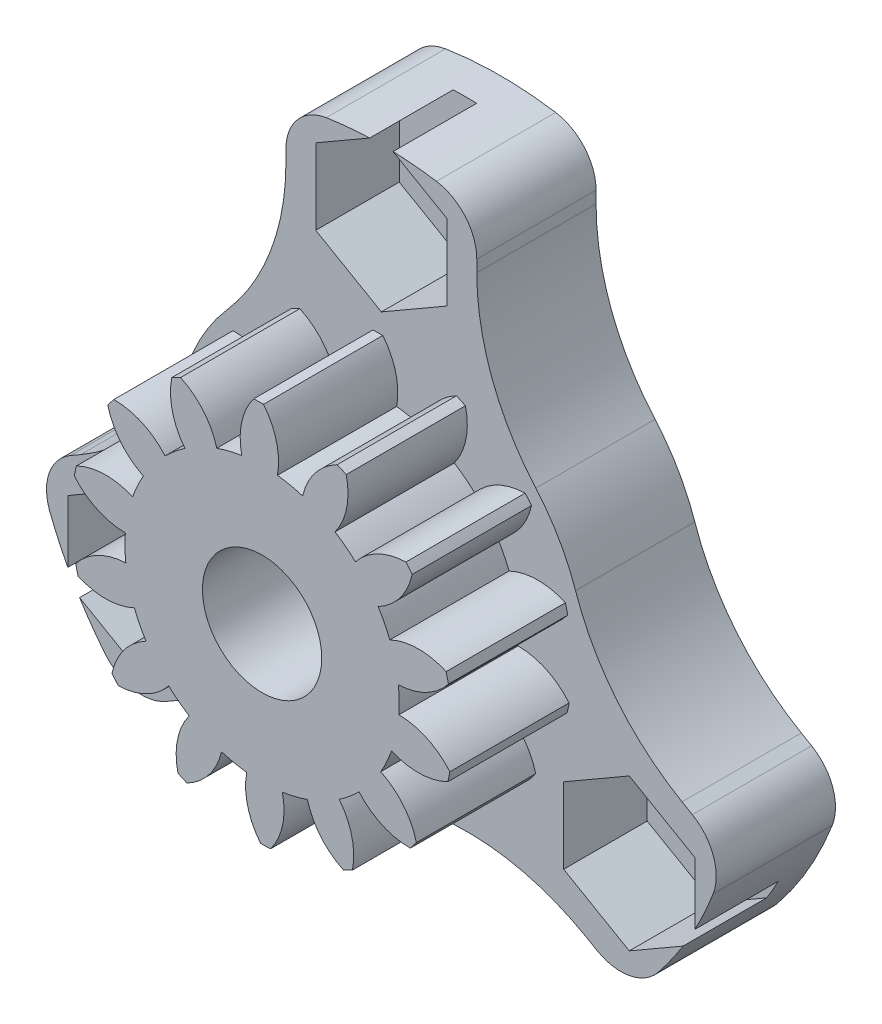
SolidWorks part; units mm, degrees
ref_plane "Front Plane" through (0, 0, 0) normal (0, 0, 1) x (1, 0, 0)
ref_plane "Top Plane" through (0, 0, 0) normal (0, 1, 0) x (1, 0, 0)
ref_plane "Right Plane" through (0, 0, 0) normal (1, 0, 0) x (0, 0, -1)
sketch "Sketch1" plane through (0, 0, 0) normal (0, 0, 1) x (1, 0, 0)
  circle A0 centre (0, 0) radius 14.9
  circle A1 centre (0, 12) radius 1.6
  circle A2 centre (10.3923, -6) radius 1.6
  circle A3 centre (-10.3923, -6) radius 1.6
  circle A4 centre (0, 0) radius 2.5
  point P11 (0, 0)
  dimension "D1" = 3
extrude "Boss-Extrude1" add sketch "Sketch1" along normal blind 5
sketch "Sketch2" plane through (0, 0, 5) normal (0, 0, 1) x (1, 0, 0)
  line L0 (13.1423, -7.5877) -> (13.1423, -4.4123)
  line L7 (0, 15.1754) -> (-2.75, 13.5877)
  line L8 (-2.75, 13.5877) -> (-2.75, 10.4123)
  line L9 (-2.75, 10.4123) -> (0, 8.8246)
  line L10 (0, 8.8246) -> (2.75, 10.4123)
  line L11 (2.75, 10.4123) -> (2.75, 13.5877)
  line L12 (2.75, 13.5877) -> (0, 15.1754)
  line L13 (13.1423, -4.4123) -> (10.3923, -2.8246)
  line L14 (10.3923, -2.8246) -> (7.6423, -4.4123)
  line L15 (7.6423, -4.4123) -> (7.6423, -7.5877)
  line L16 (7.6423, -7.5877) -> (10.3923, -9.1754)
  line L17 (10.3923, -9.1754) -> (13.1423, -7.5877)
  line L18 (-13.1423, -7.5877) -> (-10.3923, -9.1754)
  line L19 (-10.3923, -9.1754) -> (-7.6423, -7.5877)
  line L20 (-7.6423, -7.5877) -> (-7.6423, -4.4123)
  line L21 (-7.6423, -4.4123) -> (-10.3923, -2.8246)
  line L22 (-10.3923, -2.8246) -> (-13.1423, -4.4123)
  line L23 (-13.1423, -4.4123) -> (-13.1423, -7.5877)
  circle A0 centre (0, 12) radius 2.75 construction
  circle A1 centre (10.3923, -6) radius 2.75 construction
  circle A2 centre (-10.3923, -6) radius 2.75 construction
  point P27 (0, 0)
  dimension "D1" = 3
extrude "Cut-Extrude1" cut sketch "Sketch2" against normal blind 3.5
sketch "Sketch5" plane through (0, 0, 5) normal (0, 0, 1) x (1, 0, 0)
  line L7 (-8.5932, -0.3425) -> (-14.4301, -3.7124)
  line L8 (-4.5932, -7.2707) -> (-10.9038, -10.9141)
  line L9 (4.5932, -7.2707) -> (10.4301, -10.6406)
  line L10 (8.5932, -0.3425) -> (14.4301, -3.7124)
  line L11 (4, 7.6131) -> (4, 14.353)
  line L14 (-4, 7.6131) -> (-4, 14.353)
  arc A0 (-4.5932, -7.2707) -> (4.5932, -7.2707) centre (0, 0) ccw
  arc A1 (-4, 14.353) -> (-14.4301, -3.7124) centre (0, 0) ccw
  arc A2 (-4, 7.6131) -> (-8.5932, -0.3425) centre (0, 0) ccw
  arc A3 (-4, 7.6131) -> (-8.5932, -0.3425) centre (0, 0) ccw
  arc A4 (-4, 7.6131) -> (-8.5932, -0.3425) centre (0, 0) ccw
  arc A5 (14.4301, -3.7124) -> (4, 14.353) centre (0, 0) ccw
  arc A6 (8.5932, -0.3425) -> (4, 7.6131) centre (0, 0) ccw
  arc A7 (8.5932, -0.3425) -> (4, 7.6131) centre (0, 0) ccw
  arc A8 (8.5932, -0.3425) -> (4, 7.6131) centre (0, 0) ccw
  arc A9 (-10.4301, -10.6406) -> (10.4301, -10.6406) centre (0, 0) ccw
  arc A10 (-4.5932, -7.2707) -> (4.5932, -7.2707) centre (0, 0) ccw
  arc A11 (-4.5932, -7.2707) -> (4.5932, -7.2707) centre (0, 0) ccw
  point P24 (0, 0)
  arc M10 (-0.4911, 14.8919) -> (-13.1423, -7.0207) centre (0, 0) ccw
  arc M17 (-12.6512, -7.8712) -> (12.6512, -7.8712) centre (0, 0) ccw
  arc M24 (13.1423, -7.0207) -> (0.4911, 14.8919) centre (0, 0) ccw
  circle M25 centre (0, 0) radius 8.6
  dimension "D3" = 3
extrude "Cut-Extrude2" cut sketch "Sketch5" against normal through all contours L11 L10 M25 M24 | L14 L7 M25 M10 | L9 L8 M25 M17
fillet "Fillet1" radius 10 6 edges at (4, 7.6131, 2.5) (8.5932, -0.3425, 2.5) (4.5932, -7.2707, 2.5) (-4.5932, -7.2707, 2.5) (-8.5932, -0.3425, 2.5) (-4, 7.6131, 2.5)
fillet "Fillet2" radius 2 6 edges at (-14.4301, -3.7124, 2.5) (-10.4301, -10.6406, 2.5) (10.4301, -10.6406, 2.5) (14.4301, -3.7124, 2.5) (-4, 14.353, 2.5) (4, 14.353, 2.5)
sketch "Sketch6" plane through (0, 0, 5) normal (0, 0, 1) x (1, 0, 0)
  circle A0 centre (0, 0) radius 2.5
  arc A56 (6.0282, 5.2594) -> (3.9146, 4.2103) centre (6.1004, 2.4603) ccw
  arc A57 (6.2923, 4.9404) -> (6.0282, 5.2594) centre (0, 0) ccw
  arc A58 (4.8671, 3.0599) -> (6.2923, 4.9404) centre (3.5559, 5.5339) ccw
  arc A59 (5.3537, 2.0949) -> (4.8671, 3.0599) centre (0, 0) ccw
  arc A60 (7.7132, 2.123) -> (5.3537, 2.0949) centre (6.5638, -0.4302) ccw
  arc A61 (7.8127, 1.721) -> (7.7132, 2.123) centre (0, 0) ccw
  arc A62 (5.7127, 0.6451) -> (7.8127, 1.721) centre (5.6048, 3.443) ccw
  arc A63 (5.7325, -0.4355) -> (5.7127, 0.6451) centre (0, 0) ccw
  arc A64 (7.8705, -1.4338) -> (5.7325, -0.4355) centre (5.7271, -3.2355) ccw
  arc A65 (7.7857, -1.8392) -> (7.8705, -1.4338) centre (0, 0) ccw
  arc A66 (5.4269, -1.8974) -> (7.7857, -1.8392) centre (6.5436, 0.6702) ccw
  arc A67 (4.9758, -2.8796) -> (5.4269, -1.8974) centre (0, 0) ccw
  arc A68 (6.4689, -4.7067) -> (4.9758, -2.8796) centre (3.7561, -5.4) ccw
  arc A69 (6.2167, -5.0352) -> (6.4689, -4.7067) centre (0, 0) ccw
  arc A70 (4.0662, -4.0642) -> (6.2167, -5.0352) centre (6.1864, -2.2353) ccw
  arc A71 (3.2336, -4.7534) -> (4.0662, -4.0642) centre (0, 0) ccw
  arc A72 (3.7861, -7.0474) -> (3.2336, -4.7534) centre (1.0412, -6.4949) ccw
  arc A73 (3.4164, -7.2338) -> (3.7861, -7.0474) centre (0, 0) ccw
  arc A74 (1.9001, -5.4259) -> (3.4164, -7.2338) centre (4.6039, -4.6981) ccw
  arc A75 (0.851, -5.6857) -> (1.9001, -5.4259) centre (0, 0) ccw
  arc A76 (0.3535, -7.9922) -> (0.851, -5.6857) centre (-1.88, -6.3035) ccw
  arc A77 (-0.0606, -7.9998) -> (0.3535, -7.9922) centre (0, 0) ccw
  arc A78 (-0.6423, -5.713) -> (-0.0606, -7.9998) centre (2.1095, -6.2304) ccw
  arc A79 (-1.7002, -5.4918) -> (-0.6423, -5.713) centre (0, 0) ccw
  arc A80 (-3.1492, -7.3541) -> (-1.7002, -5.4918) centre (-4.4288, -4.8635) ccw
  arc A81 (-3.5256, -7.1813) -> (-3.1492, -7.3541) centre (0, 0) ccw
  arc A82 (-3.0574, -4.8686) -> (-3.5256, -7.1813) centre (-0.8027, -6.5287) ccw
  arc A83 (-3.9146, -4.2103) -> (-3.0574, -4.8686) centre (0, 0) ccw
  arc A84 (-6.0282, -5.2594) -> (-3.9146, -4.2103) centre (-6.1004, -2.4603) ccw
  arc A85 (-6.2923, -4.9404) -> (-6.0282, -5.2594) centre (0, 0) ccw
  arc A86 (-4.8671, -3.0599) -> (-6.2923, -4.9404) centre (-3.5559, -5.5339) ccw
  arc A87 (-5.3537, -2.0949) -> (-4.8671, -3.0599) centre (0, 0) ccw
  arc A88 (-7.7132, -2.123) -> (-5.3537, -2.0949) centre (-6.5638, 0.4302) ccw
  arc A89 (-7.8127, -1.721) -> (-7.7132, -2.123) centre (0, 0) ccw
  arc A90 (-5.7127, -0.6451) -> (-7.8127, -1.721) centre (-5.6048, -3.443) ccw
  arc A91 (-5.7325, 0.4355) -> (-5.7127, -0.6451) centre (0, 0) ccw
  arc A92 (-7.8705, 1.4338) -> (-5.7325, 0.4355) centre (-5.7271, 3.2355) ccw
  arc A93 (-7.7857, 1.8392) -> (-7.8705, 1.4338) centre (0, 0) ccw
  arc A94 (-5.4269, 1.8974) -> (-7.7857, 1.8392) centre (-6.5436, -0.6702) ccw
  arc A95 (-4.9758, 2.8796) -> (-5.4269, 1.8974) centre (0, 0) ccw
  arc A96 (-6.4689, 4.7067) -> (-4.9758, 2.8796) centre (-3.7561, 5.4) ccw
  arc A97 (-6.2167, 5.0352) -> (-6.4689, 4.7067) centre (0, 0) ccw
  arc A98 (-4.0662, 4.0642) -> (-6.2167, 5.0352) centre (-6.1864, 2.2353) ccw
  arc A99 (-3.2336, 4.7534) -> (-4.0662, 4.0642) centre (0, 0) ccw
  arc A100 (-3.7861, 7.0474) -> (-3.2336, 4.7534) centre (-1.0412, 6.4949) ccw
  arc A101 (-3.4164, 7.2338) -> (-3.7861, 7.0474) centre (0, 0) ccw
  arc A102 (-1.9001, 5.4259) -> (-3.4164, 7.2338) centre (-4.6039, 4.6981) ccw
  arc A103 (-0.851, 5.6857) -> (-1.9001, 5.4259) centre (0, 0) ccw
  arc A104 (-0.3535, 7.9922) -> (-0.851, 5.6857) centre (1.88, 6.3035) ccw
  arc A105 (0.0606, 7.9998) -> (-0.3535, 7.9922) centre (0, 0) ccw
  arc A106 (0.6423, 5.713) -> (0.0606, 7.9998) centre (-2.1095, 6.2304) ccw
  arc A107 (1.7002, 5.4918) -> (0.6423, 5.713) centre (0, 0) ccw
  arc A108 (3.1492, 7.3541) -> (1.7002, 5.4918) centre (4.4288, 4.8635) ccw
  arc A109 (3.5256, 7.1813) -> (3.1492, 7.3541) centre (0, 0) ccw
  arc A110 (3.0574, 4.8686) -> (3.5256, 7.1813) centre (0.8027, 6.5287) ccw
  arc A111 (3.9146, 4.2103) -> (3.0574, 4.8686) centre (0, 0) ccw
  arc A112 (6.0282, 5.2594) -> (3.9146, 4.2103) centre (6.1004, 2.4603) ccw
  arc A113 (6.2923, 4.9404) -> (6.0282, 5.2594) centre (0, 0) ccw
  arc A114 (4.8671, 3.0599) -> (6.2923, 4.9404) centre (3.5559, 5.5339) ccw
  arc A115 (5.3537, 2.0949) -> (4.8671, 3.0599) centre (0, 0) ccw
  arc A116 (7.7132, 2.123) -> (5.3537, 2.0949) centre (6.5638, -0.4302) ccw
  arc A117 (7.8127, 1.721) -> (7.7132, 2.123) centre (0, 0) ccw
  arc A118 (5.7127, 0.6451) -> (7.8127, 1.721) centre (5.6048, 3.443) ccw
  arc A119 (5.7325, -0.4355) -> (5.7127, 0.6451) centre (0, 0) ccw
  arc A120 (7.8705, -1.4338) -> (5.7325, -0.4355) centre (5.7271, -3.2355) ccw
  arc A121 (7.7857, -1.8392) -> (7.8705, -1.4338) centre (0, 0) ccw
  arc A122 (5.4269, -1.8974) -> (7.7857, -1.8392) centre (6.5436, 0.6702) ccw
  arc A123 (4.9758, -2.8796) -> (5.4269, -1.8974) centre (0, 0) ccw
  arc A124 (6.4689, -4.7067) -> (4.9758, -2.8796) centre (3.7561, -5.4) ccw
  arc A125 (6.2167, -5.0352) -> (6.4689, -4.7067) centre (0, 0) ccw
  arc A126 (4.0662, -4.0642) -> (6.2167, -5.0352) centre (6.1864, -2.2353) ccw
  arc A127 (3.2336, -4.7534) -> (4.0662, -4.0642) centre (0, 0) ccw
  arc A128 (3.7861, -7.0474) -> (3.2336, -4.7534) centre (1.0412, -6.4949) ccw
  arc A129 (3.4164, -7.2338) -> (3.7861, -7.0474) centre (0, 0) ccw
  arc A130 (1.9001, -5.4259) -> (3.4164, -7.2338) centre (4.6039, -4.6981) ccw
  arc A131 (0.851, -5.6857) -> (1.9001, -5.4259) centre (0, 0) ccw
  arc A132 (0.3535, -7.9922) -> (0.851, -5.6857) centre (-1.88, -6.3035) ccw
  arc A133 (-0.0606, -7.9998) -> (0.3535, -7.9922) centre (0, 0) ccw
  arc A134 (-0.6423, -5.713) -> (-0.0606, -7.9998) centre (2.1095, -6.2304) ccw
  arc A135 (-1.7002, -5.4918) -> (-0.6423, -5.713) centre (0, 0) ccw
  arc A136 (-3.1492, -7.3541) -> (-1.7002, -5.4918) centre (-4.4288, -4.8635) ccw
  arc A137 (-3.5256, -7.1813) -> (-3.1492, -7.3541) centre (0, 0) ccw
  arc A138 (-3.0574, -4.8686) -> (-3.5256, -7.1813) centre (-0.8027, -6.5287) ccw
  arc A139 (-3.9146, -4.2103) -> (-3.0574, -4.8686) centre (0, 0) ccw
  arc A140 (-6.0282, -5.2594) -> (-3.9146, -4.2103) centre (-6.1004, -2.4603) ccw
  arc A141 (-6.2923, -4.9404) -> (-6.0282, -5.2594) centre (0, 0) ccw
  arc A142 (-4.8671, -3.0599) -> (-6.2923, -4.9404) centre (-3.5559, -5.5339) ccw
  arc A143 (-5.3537, -2.0949) -> (-4.8671, -3.0599) centre (0, 0) ccw
  arc A144 (-7.7132, -2.123) -> (-5.3537, -2.0949) centre (-6.5638, 0.4302) ccw
  arc A145 (-7.8127, -1.721) -> (-7.7132, -2.123) centre (0, 0) ccw
  arc A146 (-5.7127, -0.6451) -> (-7.8127, -1.721) centre (-5.6048, -3.443) ccw
  arc A147 (-5.7325, 0.4355) -> (-5.7127, -0.6451) centre (0, 0) ccw
  arc A148 (-7.8705, 1.4338) -> (-5.7325, 0.4355) centre (-5.7271, 3.2355) ccw
  arc A149 (-7.7857, 1.8392) -> (-7.8705, 1.4338) centre (0, 0) ccw
  arc A150 (-5.4269, 1.8974) -> (-7.7857, 1.8392) centre (-6.5436, -0.6702) ccw
  arc A151 (-4.9758, 2.8796) -> (-5.4269, 1.8974) centre (0, 0) ccw
  arc A152 (-6.4689, 4.7067) -> (-4.9758, 2.8796) centre (-3.7561, 5.4) ccw
  arc A153 (-6.2167, 5.0352) -> (-6.4689, 4.7067) centre (0, 0) ccw
  arc A154 (-4.0662, 4.0642) -> (-6.2167, 5.0352) centre (-6.1864, 2.2353) ccw
  arc A155 (-3.2336, 4.7534) -> (-4.0662, 4.0642) centre (0, 0) ccw
  arc A156 (-3.7861, 7.0474) -> (-3.2336, 4.7534) centre (-1.0412, 6.4949) ccw
  arc A157 (-3.4164, 7.2338) -> (-3.7861, 7.0474) centre (0, 0) ccw
  arc A158 (-1.9001, 5.4259) -> (-3.4164, 7.2338) centre (-4.6039, 4.6981) ccw
  arc A159 (-0.851, 5.6857) -> (-1.9001, 5.4259) centre (0, 0) ccw
  arc A160 (-0.3535, 7.9922) -> (-0.851, 5.6857) centre (1.88, 6.3035) ccw
  arc A161 (0.0606, 7.9998) -> (-0.3535, 7.9922) centre (0, 0) ccw
  arc A162 (0.6423, 5.713) -> (0.0606, 7.9998) centre (-2.1095, 6.2304) ccw
  arc A163 (1.7002, 5.4918) -> (0.6423, 5.713) centre (0, 0) ccw
  arc A164 (3.1492, 7.3541) -> (1.7002, 5.4918) centre (4.4288, 4.8635) ccw
  arc A165 (3.5256, 7.1813) -> (3.1492, 7.3541) centre (0, 0) ccw
  arc A166 (3.0574, 4.8686) -> (3.5256, 7.1813) centre (0.8027, 6.5287) ccw
  arc A167 (3.9146, 4.2103) -> (3.0574, 4.8686) centre (0, 0) ccw
  dimension "D1" = 0
extrude "Boss-Extrude2" add sketch "Sketch6" along normal blind 5
